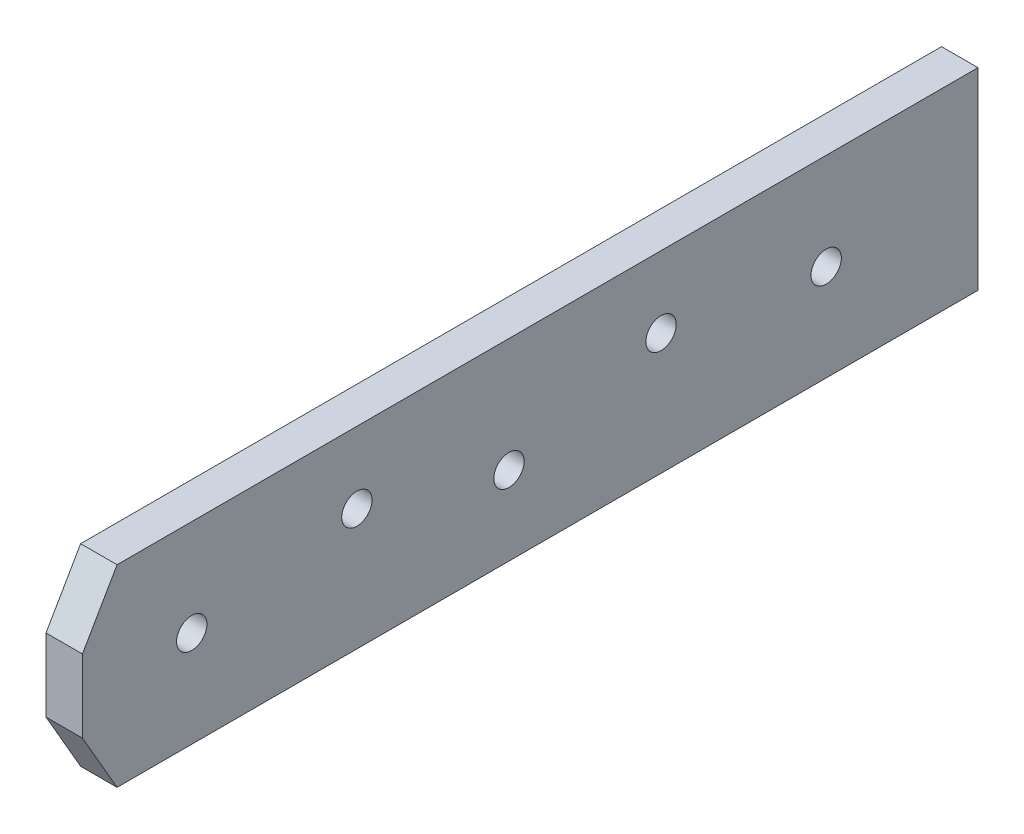
SolidWorks part; units mm, degrees
ref_plane "Front Plane" through (0, 0, 0) normal (0, 0, 1) x (1, 0, 0)
ref_plane "Top Plane" through (0, 0, 0) normal (0, 1, 0) x (1, 0, 0)
ref_plane "Right Plane" through (0, 0, 0) normal (1, 0, 0) x (0, 0, -1)
sketch "Sketch2" plane through (0, 0, 0) normal (1, 0, 0) x (0, 0, -1)
  line L0 (0, 0) -> (-25.04, 7) construction
  line L1 (-25.04, 7) -> (-52.2288, 2.875) construction
  line L2 (0, 0) -> (25.04, 7) construction
  line L3 (25.04, 7) -> (52.2288, 2.875) construction
  line L4 (-64.5275, -13) -> (-70.2288, -3.125)
  line L5 (-70.2288, 8.875) -> (-64.5275, 18.75)
  line L6 (-64.5275, 18.75) -> (77.2288, 18.75)
  line L7 (77.2288, 18.75) -> (77.2288, -13)
  line L8 (77.2288, -13) -> (-64.5275, -13)
  line L9 (-70.2288, -3.125) -> (-70.2288, 8.875)
  circle A0 centre (0, 0) radius 2.5
  circle A1 centre (-25.04, 7) radius 2.5
  circle A2 centre (-52.2288, 2.875) radius 2.5
  circle A3 centre (52.2288, 2.875) radius 2.5
  circle A4 centre (25.04, 7) radius 2.5
  point P9 (-84.3908, -7.5026)
  point P14 (-79.5807, -3.5559)
  point P20 (-76.744, -13)
  point P21 (-78.2241, 18.75)
  point P22 (-33.0608, 11.4884)
  point P23 (-66.6305, 3.7209)
  point P24 (90.0344, -13)
  point P25 (-34.0605, 8.055)
  point P26 (-55.8344, 2.7505)
  point P27 (-70.2288, 2.875)
  dimension "D1" = 5
  dimension "D2" = 26
  dimension "D4" = 31.75
  dimension "D5" = 12
  dimension "D3" = 27.5
  dimension "D6" = 13
  dimension "D7" = 60
  dimension "D8" = 18
  dimension "D9" = 25
  dimension "D10" = 20
extrude "Boss-Extrude1" add sketch "Sketch2" along normal blind 6
